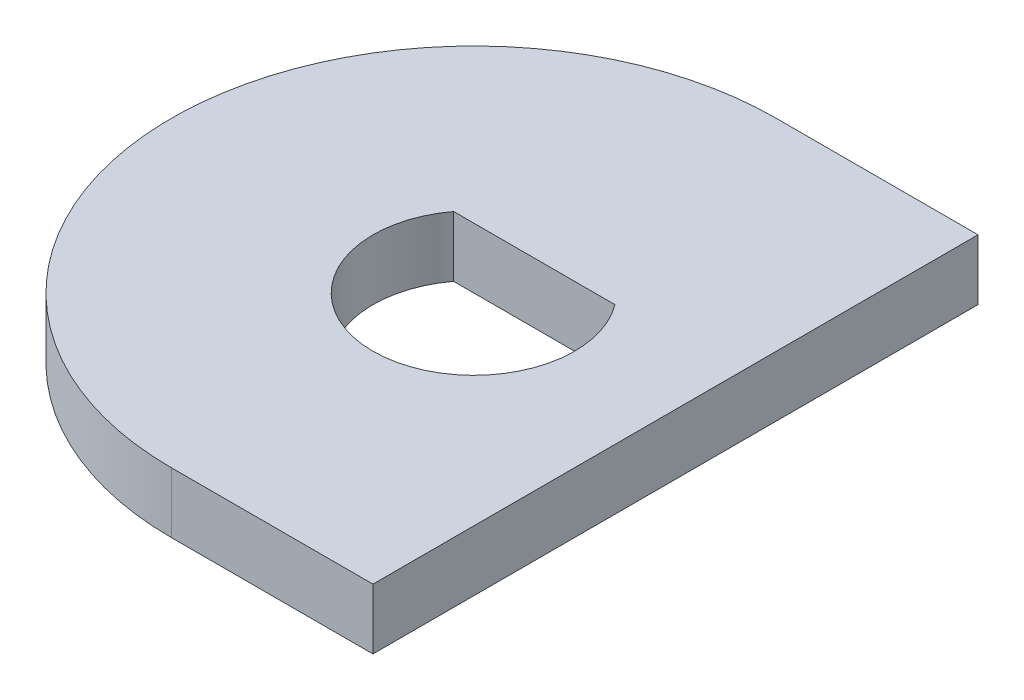
SolidWorks part; units mm, degrees
ref_plane "Front Plane" through (0, 0, 0) normal (0, 0, 1) x (1, 0, 0)
ref_plane "Top Plane" through (0, 0, 0) normal (0, 1, 0) x (1, 0, 0)
ref_plane "Right Plane" through (0, 0, 0) normal (1, 0, 0) x (0, 0, -1)
sketch "Sketch4" plane through (0, 0, 0) normal (0, 1, 0) x (1, 0, 0)
  line L0 (-7.0472, 11.8917) -> (0.9528, 11.8917)
  line L1 (-3.0472, -6.1083) -> (6.9528, -6.1083)
  line L3 (-3.0472, 23.8917) -> (6.9528, 23.8917)
  line L4 (6.9528, -6.1083) -> (6.9528, 23.8917)
  arc A0 (-3.0472, 23.8917) -> (-3.0472, -6.1083) centre (-3.0472, 8.8917) ccw
  circle A1 centre (-3.0472, 8.8917) radius 5
  point P0 (0, 0)
  dimension "D1" = 10
  dimension "D2" = 15
  dimension "D3" = 10
  dimension "D4" = 3
extrude "Boss-Extrude3" add sketch "Sketch4" along normal blind 3 contours L3 A0 L1 L4 A1 | L0 A1
